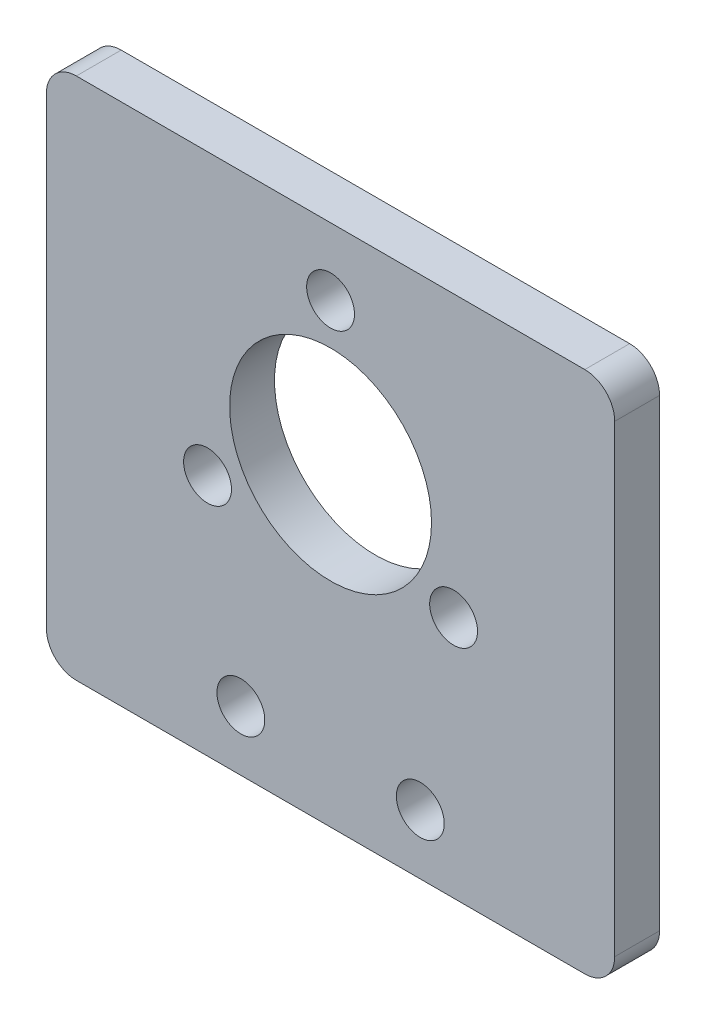
SolidWorks part; units mm, degrees
material "环氧树脂,未充填"
ref_plane "Front" through (0, 0, 0) normal (0, 0, 1) x (1, 0, 0)
ref_plane "Top" through (0, 0, 0) normal (0, 1, 0) x (1, 0, 0)
ref_plane "Right" through (0, 0, 0) normal (1, 0, 0) x (0, 0, -1)
sketch "草图1" plane through (0, 0, 0) normal (0, 0, 1) x (1, 0, 0)
  line L0 (19, 0) -> (19, -42) construction
  line L1 (2, 0) -> (36, 0)
  line L2 (0, -2) -> (0, -40)
  line L3 (2, -42) -> (36, -42)
  line L4 (38, -2) -> (38, -40)
  arc A0 (36, 0) -> (38, -2) centre (36, -2) cw
  arc A1 (0, -40) -> (2, -42) centre (2, -40) ccw
  arc A2 (36, -42) -> (38, -40) centre (36, -40) ccw
  arc A3 (2, 0) -> (0, -2) centre (2, -2) ccw
  circle A4 centre (19, -21) radius 6.75
  circle A5 centre (19, -21) radius 9.5 construction
  circle A6 centre (19, -11.5) radius 1.6
  circle A7 centre (27.2272, -25.75) radius 1.6
  circle A8 centre (10.7728, -25.75) radius 1.6
  point P7 (38, 0)
  point P10 (0, -42)
  point P15 (0, 0)
  point P29 (19, -21)
  dimension "D3" = 2
  dimension "D4" = 13.5
  dimension "D5" = 19
  dimension "D6" = 3.2
  dimension "D1" = 42
  dimension "D2" = 38
  dimension "D7" = 3
extrude "凸台-拉伸1" add sketch "草图1" along normal blind 3
sketch "草图2" plane through (0, 0, 0) normal (0, 0, -1) x (-1, 0, 0)
  line L1 (-38, -21) -> (0, -21) construction
  line L2 (-38, -40) -> (-38, -2) construction
  line L3 (0, -2) -> (0, -40) construction
  line L4 (-2, -42) -> (-36, -42) construction
  line L5 (-19, -21) -> (-19, -50021) construction
  circle A2 centre (-13, -38) radius 1.6
  circle A4 centre (-25, -38) radius 1.6
  point P2 (-19, -21)
  dimension "D1" = 12
  dimension "D2" = 4
  dimension "D3" = 3.2
extrude "切除-拉伸1" cut sketch "草图2" against normal blind 10
sketch "草图3" plane through (0, 0, 3) normal (0, 0, 1) x (1, 0, 0)
  line L0 (-8.7505, -7) -> (50.2578, -7)
  line L1 (50.2578, -7) -> (50.2578, 6.9325)
  line L2 (50.2578, 6.9325) -> (-8.7505, 6.9325)
  line L3 (-8.7505, 6.9325) -> (-8.7505, -7)
  line L4 (2, -42) -> (36, -42) construction
  dimension "D1" = 35
extrude "切除-拉伸2" cut sketch "草图3" against normal through all
fillet "圆角1" radius 2 2 edges at (38, -7, 1.5) (0, -7, 1.5)
equation "\"3。2\"=2.7"
